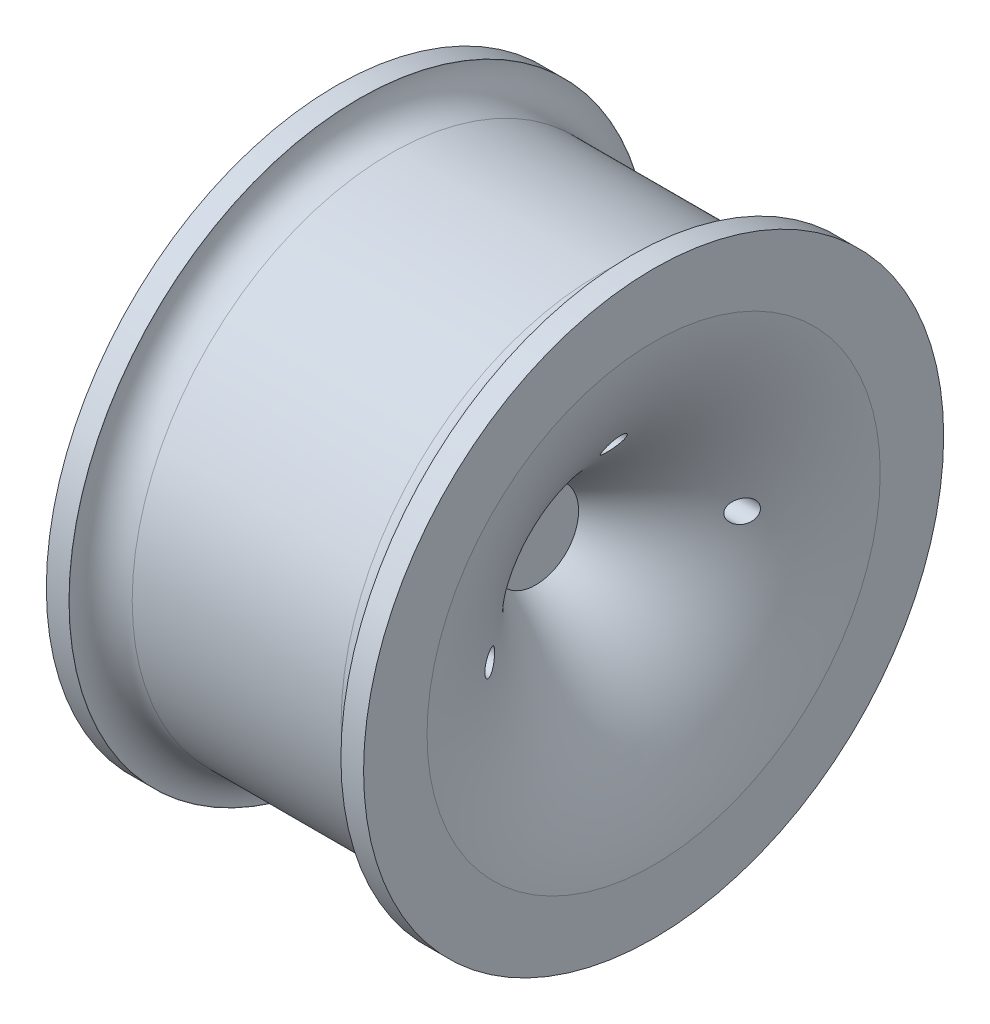
SolidWorks part; units mm, degrees
ref_plane "Plan de face" through (0, 0, 0) normal (0, 0, 1) x (1, 0, 0)
ref_plane "Plan de dessus" through (0, 0, 0) normal (0, 1, 0) x (1, 0, 0)
ref_plane "Plan de droite" through (0, 0, 0) normal (1, 0, 0) x (0, 0, -1)
sketch "Esquisse1" plane through (0, 0, 0) normal (0, 0, 1) x (1, 0, 0)
  line L0 (0, 0) -> (0, 10.3976) construction
  line L1 (-30, 50) -> (30, 50)
  line L2 (0, 5) -> (0, 10.3976) construction
  line L3 (30, 64) -> (35, 64)
  line L4 (35, 64) -> (35, 50)
  line L5 (9.532, 57) -> (23.0557, 57)
  line L6 (30, 63.9443) -> (30, 64)
  line L7 (9.532, 57) -> (-9.532, 57)
  line L8 (0, 5) -> (0, 10.3976)
  line L9 (30, 63.9443) -> (30, 64) construction
  line L10 (-30, 63.9443) -> (-30, 64) construction
  line L11 (-30, 63.9443) -> (-30, 64)
  line L12 (-9.532, 57) -> (-23.0557, 57)
  line L13 (-35, 64) -> (-35, 50)
  line L14 (-30, 64) -> (-35, 64)
  line L15 (0, 50) -> (0, 81.2457) construction
  line L16 (-30, 50) -> (-35, 50)
  line L17 (0, 0) -> (62.9053, 0) construction
  arc A0 (23.0557, 57) -> (30, 63.9443) centre (23.0557, 63.9443) ccw
  arc A1 (35, 50) -> (0, 5) centre (-19.836, 56.5391) cw
  arc A2 (29.961, 50) -> (0, 10.3976) centre (-19.836, 56.5391) cw
  arc A3 (35, 50) -> (35, 50.592) centre (35, 50.296) ccw
  arc A5 (30.0352, 50.592) -> (-1.7959, 9.6663) centre (-19.836, 56.5391) cw construction
  arc A6 (-35, 50) -> (-35, 50.592) centre (-35, 50.296) cw
  arc A9 (-23.0557, 57) -> (-30, 63.9443) centre (-23.0557, 63.9443) cw
  point P3 (0, 5)
  point P5 (9.532, 57)
  point P16 (0, 10)
  point P36 (0, 57)
  point P38 (-9.532, 57)
  dimension "D7" = 6.9443
  dimension "D1" = 50
  dimension "D2" = 5
  dimension "D3" = 30
  dimension "D4" = 14
  dimension "D5" = 5
  dimension "D6" = 7
  dimension "D9" = 5
revolve "Révolution1" add sketch "Esquisse1" angle 360 about L17
sketch "Esquisse2" plane through (-35, 0, 0) normal (-1, 0, 0) x (0, 0, 1)
  circle A0 centre (0, 0) radius 5
  circle A1 centre (0, 0) radius 10.3976
  dimension "D1" = 20.7953
  dimension "D2" = 10
extrude "Boss.-Extru.1" add sketch "Esquisse2" against normal blind 44
sketch "Esquisse3" plane through (9, 0, 0) normal (1, 0, 0) x (0, 0, -1)
  circle A0 centre (0, 0) radius 9.441
extrude "Boss.-Extru.2" add sketch "Esquisse3" against normal blind 10
sketch "Esquisse4" plane through (35, 0, 0) normal (1, 0, 0) x (0, 0, -1)
  line L0 (0, 0) -> (0, 52.0401) construction
  line L1 (-50, 0) -> (74.9912, 0) construction
  circle A0 centre (0, 0) radius 50 construction
  circle A1 centre (0, 26.0201) radius 2.5
  circle A2 centre (27.4879, 0) radius 2.5
  circle A3 centre (-29.267, 0) radius 2.5
  dimension "D1" = 5
  dimension "D2" = 5
  dimension "D3" = 5
extrude "Enlèv. mat.-Extru.1" cut sketch "Esquisse4" against normal blind 111
